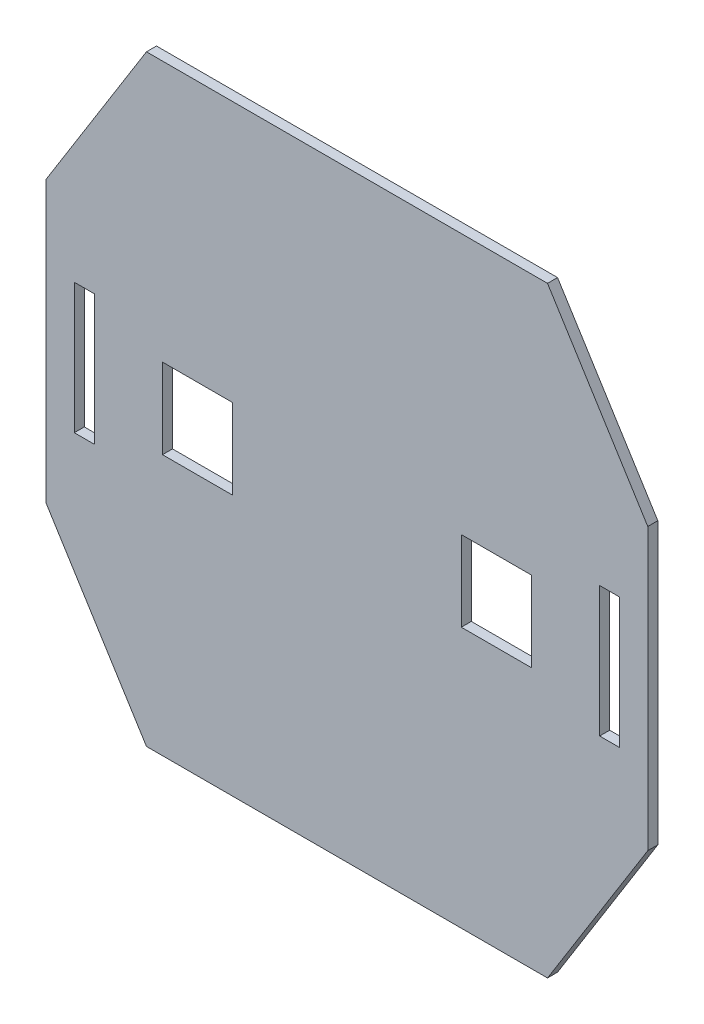
SolidWorks part; units mm, degrees
ref_plane "Front Plane" through (0, 0, 0) normal (0, 0, 1) x (1, 0, 0)
ref_plane "Top Plane" through (0, 0, 0) normal (0, 1, 0) x (1, 0, 0)
ref_plane "Right Plane" through (0, 0, 0) normal (1, 0, 0) x (0, 0, -1)
sketch "Esquisse3" plane through (0, 0, 0) normal (0, 0, 1) x (1, 0, 0)
  line L0 (0, 0) -> (0, 163.7083) construction
  line L1 (0, 0) -> (214.6618, 0) construction
  line L2 (-100, 150) -> (-150, 70)
  line L3 (100, -150) -> (-100, -150)
  line L4 (150, -70) -> (150, 70)
  line L5 (100, 150) -> (-100, 150)
  line L6 (-150, -70) -> (-150, 70)
  line L7 (147.8395, -149.0896) -> (119.7519, -118.397) construction
  line L8 (149.7748, 154.7405) -> (119.7519, 118.397) construction
  line L9 (-100, -150) -> (-150, -70)
  line L10 (100, 150) -> (150, 70)
  line L11 (100, -150) -> (150, -70)
  line L12 (-110.4962, 133.2061) -> (-138.5838, 163.8987) construction
  dimension "D1" = 300
  dimension "D2" = 300
  dimension "D3" = 50
  dimension "D4" = 80
extrude "Boss.-Extru.1" add sketch "Esquisse3" along normal blind 5
sketch "Esquisse5" plane through (0, 0, 5) normal (0, 0, 1) x (1, 0, 0)
  line L0 (0, 53.9724) -> (0, -69.5914) construction
  line L1 (-57, -20) -> (-92, -20)
  line L2 (-57, -20) -> (-57, 20)
  line L3 (-57, 20) -> (-92, 20)
  line L4 (-92, -20) -> (-92, 20)
  line L5 (-57, -20) -> (-92, 20) construction
  line L6 (-57, 20) -> (-92, -20) construction
  line L7 (57, 20) -> (92, -20) construction
  line L8 (57, -20) -> (92, 20) construction
  line L9 (92, -20) -> (92, 20)
  line L10 (57, 20) -> (92, 20)
  line L11 (57, -20) -> (92, -20)
  line L12 (57, -20) -> (57, 20)
  line L13 (135.9935, 32.5) -> (125.9935, -32.5) construction
  line L14 (-135.9935, -32.5) -> (-125.9935, -32.5)
  line L15 (-135.9935, -32.5) -> (-135.9935, 32.5)
  line L16 (-135.9935, 32.5) -> (-125.9935, 32.5)
  line L17 (-125.9935, -32.5) -> (-125.9935, 32.5)
  line L18 (-135.9935, -32.5) -> (-125.9935, 32.5) construction
  line L19 (-135.9935, 32.5) -> (-125.9935, -32.5) construction
  line L20 (135.9935, -32.5) -> (125.9935, 32.5) construction
  line L21 (135.9935, 32.5) -> (125.9935, 32.5)
  line L22 (135.9935, -32.5) -> (135.9935, 32.5)
  line L23 (135.9935, -32.5) -> (125.9935, -32.5)
  line L24 (125.9935, -32.5) -> (125.9935, 32.5)
  point P0 (-74.5, 0)
  point P12 (74.5, 0)
  point P13 (-130.9935, 0)
  point P22 (130.9935, 0)
  dimension "D1" = 35
  dimension "D2" = 40
  dimension "D3" = 57
  dimension "D4" = 10
  dimension "D5" = 65
extrude "Enlèv. mat.-Extru.1" cut sketch "Esquisse5" against normal blind 20
